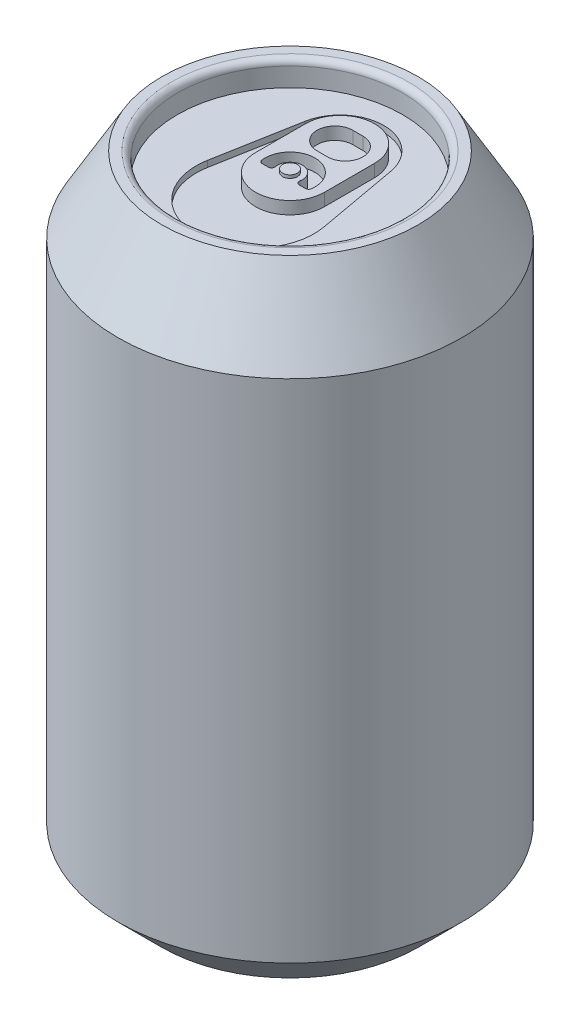
SolidWorks part; units mm, degrees
ref_plane "Front" through (0, 0, 0) normal (0, 0, 1) x (1, 0, 0)
ref_plane "Top" through (0, 0, 0) normal (0, 1, 0) x (1, 0, 0)
ref_plane "Right" through (0, 0, 0) normal (1, 0, 0) x (0, 0, -1)
sketch "Sketch1" plane through (0, 0, 0) normal (0, 1, 0) x (1, 0, 0)
  circle A0 centre (0, 0) radius 27.5
  dimension "D1" = 55
extrude "Boss-Extrude1" add sketch "Sketch1" along normal blind 100
chamfer "Chamfer1" distance 7 angle 60 1 edges at (0, 100, 27.5)
chamfer "Chamfer2" distance 7 angle 45 1 edges at (0, 0, 27.5)
sketch "Sketch2" plane through (0, 100, 0) normal (0, 1, 0) x (1, 0, 0)
  circle A2 centre (0, 0) radius 18
  circle A3 centre (0, 0) radius 18
  dimension "D1" = 2.5
extrude "Cut-Extrude1" cut sketch "Sketch2" against normal blind 4
fillet "Fillet1" radius 1 1 edges at (0, 100, 18)
sketch "Sketch3" plane through (0, 96, 0) normal (0, 1, 0) x (1, 0, 0)
  line L0 (0, 0) -> (0, 8) construction
  line L1 (0, 0) -> (0, -5.5782) construction
  line L2 (-9.2707, -3.8977) -> (-6.8878, 9.2485)
  line L3 (9.2707, -3.8977) -> (6.8878, 9.2485)
  line L4 (0, 0) -> (0, 8) construction
  line L5 (-5.5, 0) -> (-5.5, 8)
  line L6 (5.5, 0) -> (5.5, 8)
  line L7 (-5.5, 8) -> (5.5, 8) construction
  line L8 (-0.8242, 8) -> (0.8242, 8) construction
  line L9 (-0.8242, 10.8534) -> (0.8242, 10.8534)
  line L10 (-0.8242, 5.1466) -> (0.8242, 5.1466)
  line L11 (3.873, -1) -> (-3.873, -1) construction
  line L12 (-1.7321, -1) -> (-3.873, -1)
  line L13 (1.7321, -1) -> (3.873, -1)
  circle A0 centre (0, -5.5782) radius 9.4218 construction
  circle A1 centre (0, 8) radius 7 construction
  circle A2 centre (0, 0) radius 15 construction
  circle A3 centre (0, 0) radius 18 construction
  circle A4 centre (0, 0) radius 18 construction
  arc A5 (-9.2707, -3.8977) -> (9.2556, -3.8162) centre (0, -5.5782) ccw
  arc A6 (-6.8878, 9.2485) -> (6.9052, 9.1482) centre (0, 8) cw
  arc A7 (-5.5, 0) -> (5.5, 0) centre (0, 0) ccw
  arc A8 (5.5, 8) -> (-5.5, 8) centre (0, 8) ccw
  arc A9 (-0.8242, 10.8534) -> (-0.8242, 5.1466) centre (-0.8242, 8) ccw
  arc A10 (0.8242, 5.1466) -> (0.8242, 10.8534) centre (0.8242, 8) ccw
  circle A11 centre (0, 0) radius 2
  circle A12 centre (0, 0) radius 4
  point P16 (0, 4)
  point P24 (0, 8)
  point P26 (0, 8)
  dimension "D1" = 3
  dimension "D2" = 1.5
  dimension "D3" = 7
  dimension "D4" = 2.8534
  dimension "D6" = 4
  dimension "D8" = 9.4218
  dimension "D5" = 1.6485
  dimension "D7" = 1
sketch "Sketch4" plane through (0, 96, 0) normal (0, 1, 0) x (1, 0, 0)
  line L0 (9.2707, -3.8977) -> (6.8878, 9.2485) construction
  line L1 (-9.2707, -3.8977) -> (-6.8878, 9.2485) construction
  line L2 (9.2707, -3.8977) -> (6.8878, 9.2485)
  line L3 (-9.2707, -3.8977) -> (-6.8878, 9.2485)
  arc A0 (-9.2707, -3.8977) -> (9.2556, -3.8162) centre (0, -5.5782) ccw construction
  arc A1 (6.9052, 9.1482) -> (-6.8878, 9.2485) centre (0, 8) ccw construction
  arc A2 (-9.2707, -3.8977) -> (9.2556, -3.8162) centre (0, -5.5782) ccw
  arc A3 (6.9052, 9.1482) -> (-6.8878, 9.2485) centre (0, 8) ccw
extrude "Cut-Extrude2" cut sketch "Sketch4" against normal blind 1
sketch "Sketch6" plane through (0, 95, 0) normal (0, 1, 0) x (1, 0, 0)
  line L0 (-5.5, 0) -> (-5.5, 8) construction
  line L1 (-5.5, 0) -> (-5.5, 8)
  line L3 (5.5, 0) -> (5.5, 8) construction
  line L4 (5.5, 0) -> (5.5, 8)
  line L5 (-0.8242, 10.8534) -> (0.8242, 10.8534) construction
  line L6 (-0.8242, 5.1466) -> (0.8242, 5.1466) construction
  line L7 (-0.8242, 10.8534) -> (0.8242, 10.8534)
  line L8 (-0.8242, 5.1466) -> (0.8242, 5.1466)
  line L9 (1.7321, -1) -> (3.873, -1) construction
  line L10 (-1.7321, -1) -> (-3.873, -1) construction
  line L11 (1.7321, -1) -> (3.873, -1)
  line L12 (-1.7321, -1) -> (-3.873, -1)
  arc A0 (-5.5, 0) -> (5.5, 0) centre (0, 0) ccw construction
  arc A1 (-5.5, 0) -> (5.5, 0) centre (0, 0) ccw
  arc A2 (5.5, 8) -> (-5.5, 8) centre (0, 8) ccw construction
  arc A3 (5.5, 8) -> (-5.5, 8) centre (0, 8) ccw
  arc A4 (-0.8242, 10.8534) -> (-0.8242, 5.1466) centre (-0.8242, 8) ccw construction
  arc A5 (-0.8242, 10.8534) -> (-0.8242, 5.1466) centre (-0.8242, 8) ccw
  arc A6 (0.8242, 5.1466) -> (0.8242, 10.8534) centre (0.8242, 8) ccw construction
  arc A7 (0.8242, 5.1466) -> (0.8242, 10.8534) centre (0.8242, 8) ccw
  circle A8 centre (0, 0) radius 2 construction
  circle A9 centre (0, 0) radius 4 construction
  circle A10 centre (0, 0) radius 2
  arc A11 (3.873, -1) -> (-3.873, -1) centre (0, 0) ccw
extrude "Boss-Extrude2" add sketch "Sketch6" along normal blind 2 contours L4 A3 L1 A1 A11 L11 A10 L12 A7 L8 A5 L7 | A10
fillet "Fillet2" radius 0.5 4 edges at (1.7321, 96, 1) (-1.7321, 96, 1) (3.873, 96, 1) (-3.873, 96, 1)
sketch "Sketch7" plane through (0, 97, 0) normal (0, 1, 0) x (1, 0, 0)
  circle A0 centre (0, 0) radius 1.1853
extrude "Boss-Extrude3" add sketch "Sketch7" along normal blind 0.5
